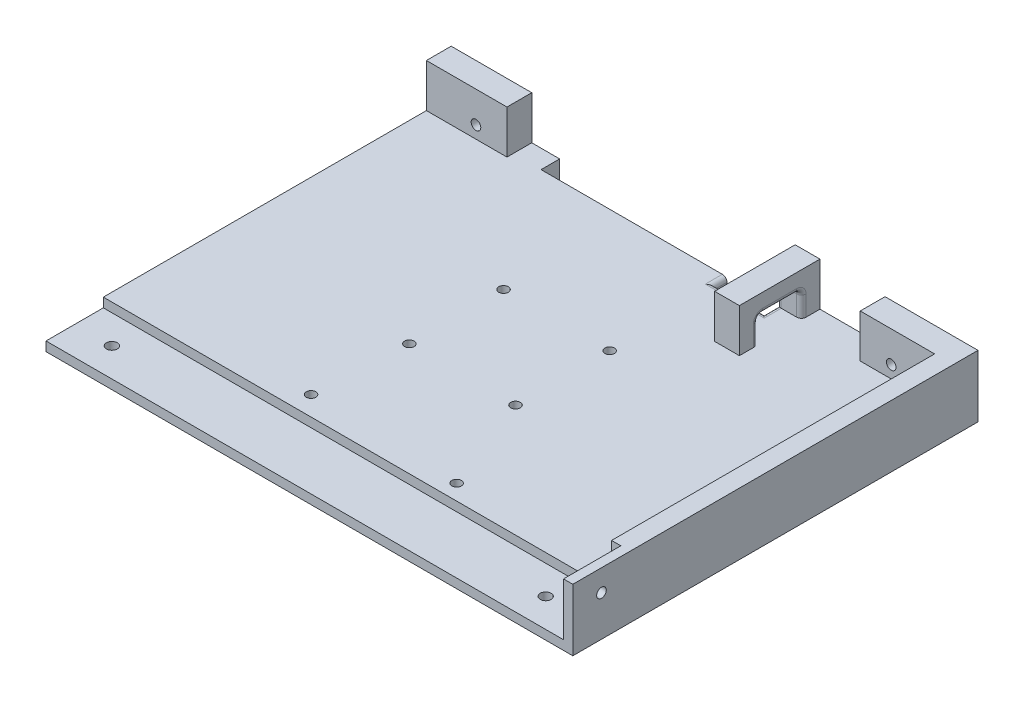
SolidWorks part; units mm, degrees
ref_plane "Front" through (0, 0, 0) normal (0, 0, 1) x (1, 0, 0)
ref_plane "Top" through (0, 0, 0) normal (0, 1, 0) x (1, 0, 0)
ref_plane "Right" through (0, 0, 0) normal (1, 0, 0) x (0, 0, -1)
sketch "Sketch1" plane through (0, 0, 0) normal (0, 1, 0) x (1, 0, 0)
  line L1 (-85, -65.375) -> (85, -65.375)
  line L2 (-85, -65.375) -> (-85, 65.375)
  line L3 (-85, 65.375) -> (85, 65.375)
  line L4 (85, -65.375) -> (85, 65.375)
  line L5 (-85, -65.375) -> (85, 65.375) construction
  line L6 (-85, 65.375) -> (85, -65.375) construction
  line L7 (-50, 65.375) -> (10, 65.375)
  line L8 (-50, 65.375) -> (-50, 59.375)
  line L9 (-50, 59.375) -> (10, 59.375)
  line L10 (10, 65.375) -> (10, 59.375)
  line L11 (-50, 65.375) -> (10, 59.375) construction
  line L12 (-50, 59.375) -> (10, 65.375) construction
  point P0 (0, 0)
  point P10 (-20, 62.375)
  dimension "D1" = 130.75
  dimension "D2" = 170
  dimension "D3" = 6
  dimension "D4" = 60
  dimension "D5" = 35
extrude "Boss-Extrude1" add sketch "Sketch1" along normal blind 6 contours L3 L10 L9 L8 L2 L1 L4
sketch "Sketch2" plane through (0, 6, 0) normal (0, 1, 0) x (1, 0, 0)
  line L0 (10, 65.375) -> (85, 65.375) construction
  line L1 (-85, 65.375) -> (-59, 65.375)
  line L2 (-85, 65.375) -> (-85, 57.375)
  line L3 (-85, 57.375) -> (-59, 57.375)
  line L4 (-59, 65.375) -> (-59, 57.375)
  line L5 (-85, 65.375) -> (-59, 57.375) construction
  line L6 (-85, 57.375) -> (-59, 65.375) construction
  line L7 (85, 65.375) -> (55, 65.375)
  line L8 (85, 65.375) -> (85, 57.375)
  line L9 (85, 57.375) -> (55, 57.375)
  line L10 (55, 65.375) -> (55, 57.375)
  line L11 (85, 65.375) -> (55, 57.375) construction
  line L12 (85, 57.375) -> (55, 65.375) construction
  point P4 (-72, 61.375)
  point P10 (70, 61.375)
  dimension "D1" = 8
  dimension "D2" = 26
  dimension "D3" = 8
  dimension "D4" = 30
extrude "Boss-Extrude2" add sketch "Sketch2" along normal blind 14
sketch "Sketch3" plane through (0, 0, -57.375) normal (0, 0, 1) x (1, 0, 0)
  line L0 (-85, 20) -> (-59, 20) construction
  line L2 (-59, 20) -> (-59, 6) construction
  line L3 (55, 20) -> (85, 20) construction
  line L4 (55, 20) -> (55, 6) construction
  circle A0 centre (-69, 10) radius 1.55
  circle A1 centre (65, 10) radius 1.55
  dimension "D1" = 3.1
  dimension "D2" = 10
  dimension "D3" = 10
  dimension "D4" = 3.1
  dimension "D5" = 10
  dimension "D6" = 10
extrude "Cut-Extrude1" cut sketch "Sketch3" against normal through all
sketch "Sketch4" plane through (0, 6, 0) normal (0, 1, 0) x (1, 0, 0)
  line L0 (85, -65.375) -> (85, 57.375) construction
  line L1 (-85, -65.375) -> (85, -65.375)
  line L2 (-85, -65.375) -> (-85, -46.875)
  line L3 (-85, -46.875) -> (85, -46.875)
  line L4 (85, -65.375) -> (85, -46.875)
  line L5 (-85, -65.375) -> (85, -46.875) construction
  line L6 (-85, -46.875) -> (85, -65.375) construction
  point P4 (0, -56.125)
  dimension "D1" = 18.5
extrude "Cut-Extrude2" cut sketch "Sketch4" against normal blind 3
sketch "Sketch5" plane through (0, 3, 0) normal (0, 1, 0) x (1, 0, 0)
  line L0 (-85, -46.875) -> (-85, -65.375) construction
  line L1 (85, -65.375) -> (85, -46.875) construction
  line L2 (-85, -65.375) -> (85, -65.375) construction
  circle A0 centre (-73, -56.125) radius 1.75
  circle A1 centre (67, -56.125) radius 1.75
  dimension "D1" = 3.5
  dimension "D2" = 3.5
  dimension "D3" = 12
  dimension "D5" = 9.25
  dimension "D4" = 18
extrude "Cut-Extrude3" cut sketch "Sketch5" against normal blind 3
sketch "Sketch7" plane through (0, 20, 0) normal (0, 1, 0) x (1, 0, 0)
  line L0 (-85, -65.375) -> (85, -65.375) construction
  line L1 (85, 65.375) -> (79, 65.375)
  line L2 (85, 65.375) -> (85, -65.375)
  line L3 (85, -65.375) -> (79, -65.375)
  line L4 (79, 65.375) -> (79, -65.375)
  line L5 (85, 65.375) -> (79, -65.375) construction
  line L6 (85, -65.375) -> (79, 65.375) construction
  line L7 (85, -46.875) -> (-85, -46.875) construction
  line L8 (79, -65.375) -> (82, -65.375)
  line L9 (79, -65.375) -> (79, -46.875)
  line L10 (79, -46.875) -> (82, -46.875)
  line L11 (82, -65.375) -> (82, -46.875)
  line L12 (79, -65.375) -> (82, -46.875) construction
  line L13 (79, -46.875) -> (82, -65.375) construction
  line L14 (85, -46.875) -> (-85, -46.875) construction
  point P4 (82, 0)
  point P11 (80.5, -56.125)
  line M5 (55, 57.375) -> (85, 57.375)
  dimension "D1" = 6
  dimension "D2" = 3
extrude "Boss-Extrude3" add sketch "Sketch7" against normal up to next contours L11 L3 L2 L4 L10 M5
sketch "Sketch8" plane through (82, 0, 0) normal (-1, 0, 0) x (0, 0, 1)
  line L1 (65.375, 20) -> (46.875, 20) construction
  line L2 (65.375, 20) -> (65.375, 6) construction
  line L3 (65.375, 6) -> (46.875, 6) construction
  line L4 (46.875, 20) -> (46.875, 6) construction
  line L5 (65.375, 20) -> (46.875, 6) construction
  line L6 (65.375, 6) -> (46.875, 20) construction
  circle A0 centre (56.125, 13) radius 1.55
  point P4 (56.125, 13)
  dimension "D1" = 3.1
extrude "Cut-Extrude4" cut sketch "Sketch8" against normal through all
sketch "Sketch9" plane through (0, 6, 0) normal (0, 1, 0) x (1, 0, 0)
  line L1 (10, 65.375) -> (26, 65.375)
  line L2 (10, 65.375) -> (10, 55.375)
  line L3 (10, 55.375) -> (26, 55.375)
  line L4 (26, 65.375) -> (26, 55.375)
  line L5 (10, 65.375) -> (26, 55.375) construction
  line L6 (10, 55.375) -> (26, 65.375) construction
  point P4 (18, 60.375)
  dimension "D1" = 10
  dimension "D2" = 16
extrude "Cut-Extrude5" cut sketch "Sketch9" against normal up to next
sketch "Sketch10" plane through (0, 6, 0) normal (0, 1, 0) x (1, 0, 0)
  line L1 (26, 65.375) -> (34, 65.375)
  line L2 (26, 65.375) -> (26, 39.375)
  line L3 (26, 39.375) -> (34, 39.375)
  line L4 (34, 65.375) -> (34, 39.375)
  line L5 (26, 65.375) -> (34, 39.375) construction
  line L6 (26, 39.375) -> (34, 65.375) construction
  point P4 (30, 52.375)
  dimension "D1" = 26
  dimension "D2" = 8
extrude "Boss-Extrude4" add sketch "Sketch10" along normal blind 14
sketch "Sketch11" plane through (34, 0, 0) normal (1, 0, 0) x (0, 0, -1)
  line L4 (45.375, 12) -> (45.375, 6)
  line L5 (39.375, 6) -> (65.375, 6) construction
  line L6 (45.375, 6) -> (59.375, 6)
  line L7 (59.375, 6) -> (59.375, 12)
  line L8 (45.375, 12) -> (59.375, 12)
  line L9 (59.375, 12) -> (59.375, 14)
  line L10 (59.375, 14) -> (45.375, 14)
  line L11 (45.375, 14) -> (45.375, 12)
  line L13 (59.375, 12) -> (59.375, 14)
  line L14 (59.375, 14) -> (45.375, 14)
  line L15 (45.375, 14) -> (45.375, 12)
  dimension "D1" = 6
extrude "Cut-Extrude6" cut sketch "Sketch11" against normal up to next
fillet "Fillet1" radius 1.5 11 edges at (30, 14, -59.375) (30, 14, -45.375) (26, 10, -45.375) (26, 14, -52.375) (10, 6, -57.375) (18, 6, -55.375) (26, 6, -57.375) (26, 10, -59.375) (34, 10, -59.375) (34, 14, -52.375) (34, 10, -45.375)
sketch "Sketch12" plane through (0, 6, 0) normal (0, 1, 0) x (1, 0, 0)
  line L0 (79, 57.375) -> (79, -46.875) construction
  line L1 (79, -46.875) -> (-85, -46.875) construction
  circle A0 centre (24, -41.875) radius 1.55
  circle A1 centre (-24.26, -40.575) radius 1.55
  dimension "D1" = 3.1
  dimension "D2" = 3.1
  dimension "D3" = 55
  dimension "D4" = 1.3
  dimension "D5" = 48.26
  dimension "D6" = 5
extrude "Cut-Extrude7" cut sketch "Sketch12" against normal blind 14
sketch "Sketch13" plane through (0, 6, 0) normal (0, 1, 0) x (1, 0, 0)
  circle A0 centre (11.6852, 19.8285) radius 1.55
  circle A1 centre (-22.5604, 19.8285) radius 1.55
  circle A2 centre (11.6852, -10.5445) radius 1.55
  circle A3 centre (-22.5604, -10.5445) radius 1.55
  point P8 (-22.5604, 19.8285)
  point P9 (11.6852, -10.5445)
  point P10 (-15.6942, 8.9506)
  point P11 (-22.5604, 19.8285)
  dimension "D1" = 3.1
  dimension "D2" = 3.1
  dimension "D3" = 3.1
  dimension "D4" = 3.1
extrude "Cut-Extrude8" cut sketch "Sketch13" against normal up to next
